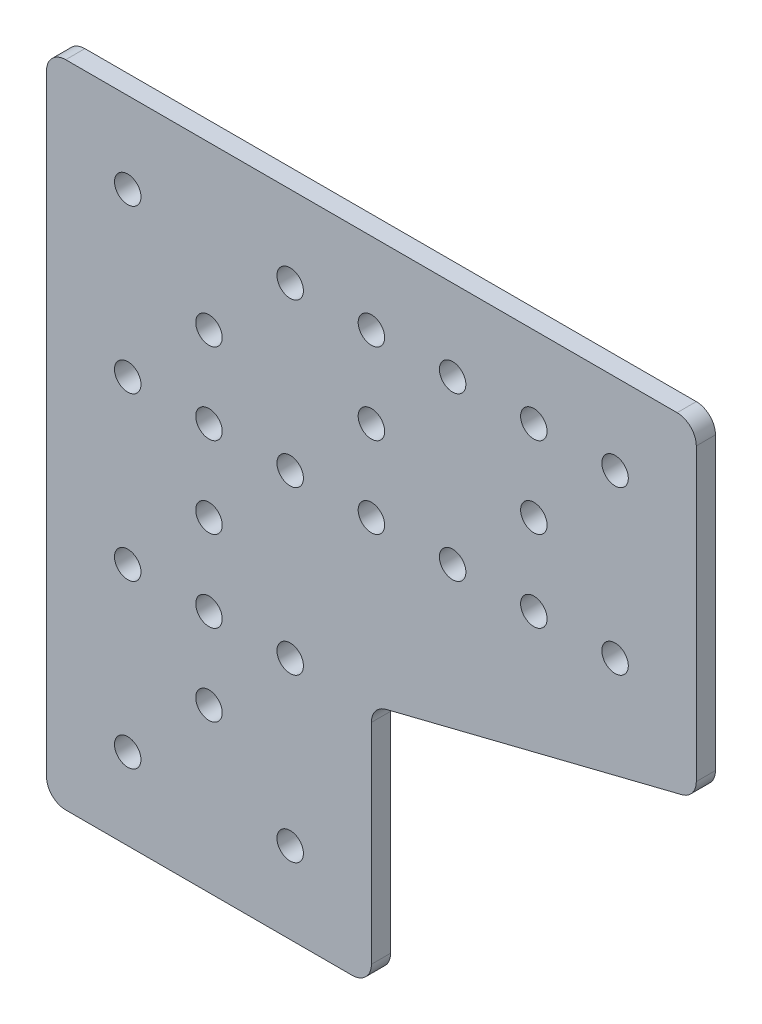
SolidWorks part; units mm, degrees
ref_plane "Front Plane" through (0, 0, 0) normal (0, 0, 1) x (1, 0, 0)
ref_plane "Top Plane" through (0, 0, 0) normal (0, 1, 0) x (1, 0, 0)
ref_plane "Right Plane" through (0, 0, 0) normal (1, 0, 0) x (0, 0, -1)
sketch "Sketch3" plane through (0, 0, 0) normal (0, 0, 1) x (1, 0, 0)
  line L1 (0, 0) -> (0, -101.6)
  line L2 (0, -101.6) -> (50.8, -101.6)
  line L3 (50.8, -101.6) -> (50.8, -63.5)
  line L4 (50.8, -63.5) -> (101.6, -50.8)
  line L5 (101.6, -50.8) -> (101.6, 0)
  line L6 (50.8, -63.5) -> (50.8, 0) construction
  line L7 (0, 0) -> (50.8, 0)
  line L8 (50.8, 0) -> (101.6, 0)
  line L9 (25.4, -101.6) -> (25.4, 0) construction
  line L10 (0, -88.9) -> (12.7, -88.9) construction
  line L11 (12.7, -88.9) -> (12.7, -101.6) construction
  line L12 (101.6, -25.4) -> (25.4, -25.4) construction
  circle A0 centre (12.7, -88.9) radius 2.07
  circle A1 centre (12.7, -63.5) radius 2.07
  circle A2 centre (12.7, -38.1) radius 2.07
  circle A3 centre (12.7, -12.7) radius 2.07
  circle A4 centre (38.1, -12.7) radius 2.07
  circle A5 centre (38.1, -38.1) radius 2.07
  circle A6 centre (38.1, -63.5) radius 2.07
  circle A7 centre (38.1, -88.9) radius 2.07
  circle A8 centre (25.4, -76.2) radius 2.07
  circle A9 centre (25.4, -63.5) radius 2.07
  circle A10 centre (25.4, -50.8) radius 2.07
  circle A11 centre (25.4, -38.1) radius 2.07
  circle A12 centre (25.4, -25.4) radius 2.07
  circle A13 centre (50.8, -12.7) radius 2.07
  circle A14 centre (50.8, -38.1) radius 2.07
  circle A15 centre (63.5, -12.7) radius 2.07
  circle A16 centre (63.5, -38.1) radius 2.07
  circle A17 centre (76.2, -12.7) radius 2.07
  circle A18 centre (76.2, -38.1) radius 2.07
  circle A19 centre (88.9, -12.7) radius 2.07
  circle A20 centre (88.9, -38.1) radius 2.07
  circle A21 centre (50.8, -25.4) radius 2.07
  circle A22 centre (76.2, -25.4) radius 2.07
  dimension "D9" = 4.14
  dimension "D15" = 3
  dimension "D1" = 50.8
  dimension "D2" = 101.6
  dimension "D3" = 50.8
  dimension "D4" = 50.8
  dimension "D5" = 38.1
  dimension "D6" = 12.7
  dimension "D8" = 25.4
  dimension "D10" = 25.4
  dimension "D12" = 12.7
  dimension "D14" = 12.7
  dimension "D16" = 25.4
  dimension "D7" = 4
  dimension "D11" = 5
  dimension "D13" = 5
extrude "Boss-Extrude1" add sketch "Sketch3" along normal mid plane 3
fillet "Fillet1" radius 3 6 edges at (101.6, -50.8, 0) (50.8, -63.5, 0) (50.8, -101.6, 0) (0, -101.6, 0) (0, 0, 0) (101.6, 0, 0)
